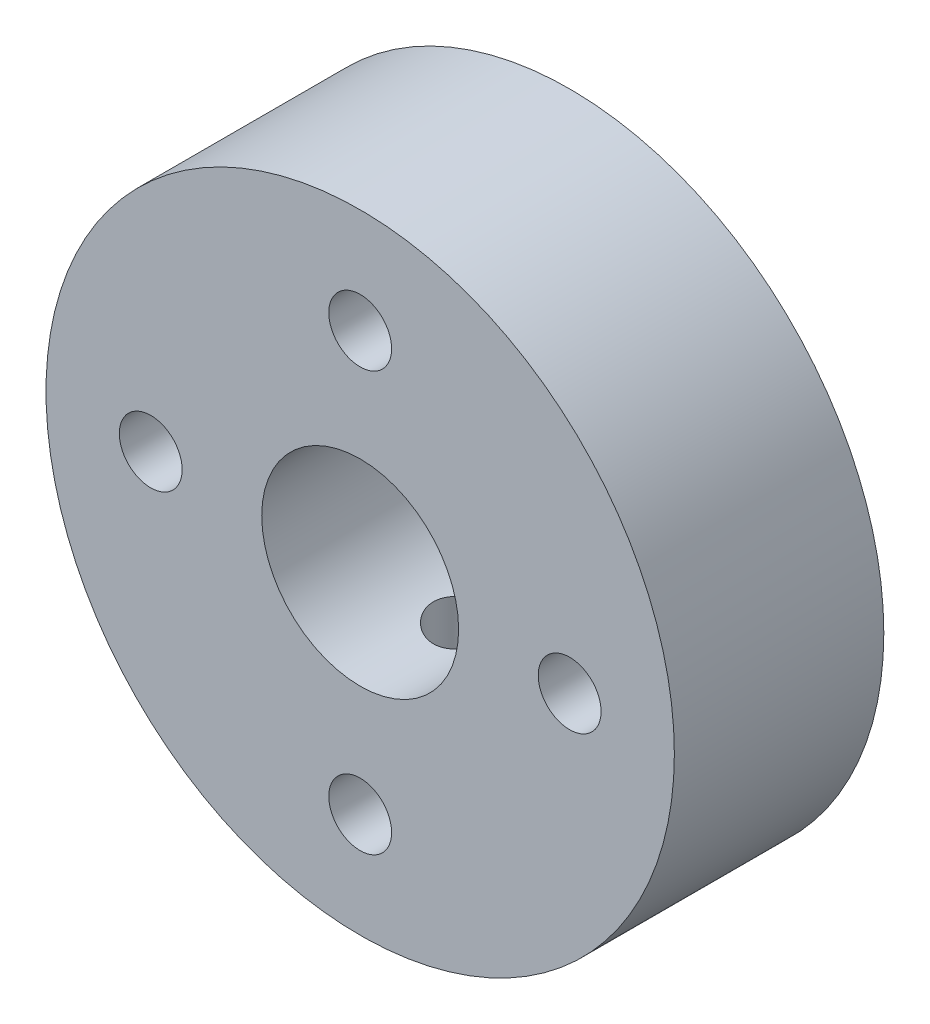
SolidWorks part; units mm, degrees
ref_plane "Front Plane" through (0, 0, 0) normal (0, 0, 1) x (1, 0, 0)
ref_plane "Top Plane" through (0, 0, 0) normal (0, 1, 0) x (1, 0, 0)
ref_plane "Right Plane" through (0, 0, 0) normal (1, 0, 0) x (0, 0, -1)
sketch "Sketch1" plane through (0, 0, 0) normal (0, 0, 1) x (1, 0, 0)
  circle A0 centre (0, 10) radius 1.5
  circle A1 centre (0, 0) radius 15
  circle A6 centre (0, 0) radius 4.7
  circle A7 centre (10, 0) radius 1.5
  circle A8 centre (0, -10) radius 1.5
  circle A9 centre (-10, 0) radius 1.5
  dimension "D1" = 4
extrude "Boss-Extrude2" add sketch "Sketch1" along normal blind 10
sketch "Sketch2" plane through (0, 0, 0) normal (0, 1, 0) x (1, 0, 0)
  circle A0 centre (0, -5) radius 1.5
extrude "Cut-Extrude1" cut sketch "Sketch2" against normal blind 35
